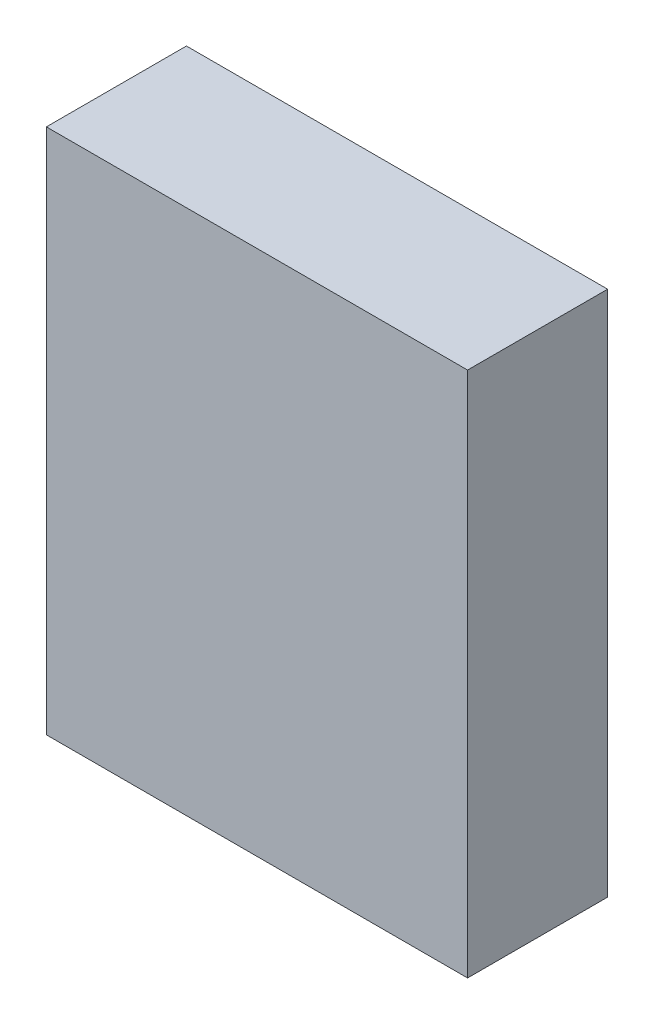
SolidWorks part; units mm, degrees
material "AISI 1045 Steel, cold drawn"
ref_plane "Front Plane" through (0, 0, 0) normal (0, 0, 1) x (1, 0, 0)
ref_plane "Top Plane" through (0, 0, 0) normal (0, 1, 0) x (1, 0, 0)
ref_plane "Right Plane" through (0, 0, 0) normal (1, 0, 0) x (0, 0, -1)
sketch "Sketch1" plane through (0, 0, 0) normal (0, 0, 1) x (1, 0, 0)
  line L1 (200, -250) -> (-200, -250)
  line L2 (200, -250) -> (200, 250)
  line L3 (200, 250) -> (-200, 250)
  line L4 (-200, -250) -> (-200, 250)
  line L5 (200, -250) -> (-200, 250) construction
  line L6 (200, 250) -> (-200, -250) construction
  point P0 (0, 0)
  dimension "D1" = 500
  dimension "D2" = 400
extrude "Boss-Extrude1" add sketch "Sketch1" along normal blind 150
sketch "Sketch2" plane through (0, 0, 0) normal (0, 0, -1) x (-1, 0, 0)
  line L1 (177.5, -230) -> (-177.5, -230)
  line L2 (177.5, -230) -> (177.5, 230)
  line L3 (177.5, 230) -> (-177.5, 230)
  line L4 (200, -250) -> (200, 250)
  line L5 (200, 250) -> (-200, 250)
  line L6 (-200, 250) -> (-200, -250)
  line L7 (-200, -250) -> (200, -250)
  line L8 (200, -250) -> (200, 250)
  line L9 (200, 250) -> (-200, 250)
  line L10 (-200, 250) -> (-200, -250)
  line L11 (-200, -250) -> (200, -250)
  line L12 (-177.5, -230) -> (-177.5, 230)
  line L13 (177.5, -230) -> (-177.5, 230) construction
  line L14 (177.5, 230) -> (-177.5, -230) construction
  point P2 (0, 0)
  dimension "D2" = 355
  dimension "D3" = 460
  dimension "D1" = 0
extrude "Cut-Extrude1" cut sketch "Sketch2" against normal blind 17
shell "Shell1" thickness 1.5
sketch "Sketch3" plane through (0, 0, 148.5) normal (0, 0, -1) x (-1, 0, 0)
  line L1 (162.5, -202.5) -> (-162.5, -202.5) construction
  line L2 (162.5, -202.5) -> (162.5, 202.5) construction
  line L3 (162.5, 202.5) -> (-162.5, 202.5) construction
  line L4 (-162.5, -202.5) -> (-162.5, 202.5) construction
  line L5 (162.5, -202.5) -> (-162.5, 202.5) construction
  line L6 (162.5, 202.5) -> (-162.5, -202.5) construction
  circle A0 centre (-162.5, 202.5) radius 7.5
  circle A1 centre (162.5, 202.5) radius 7.5
  circle A2 centre (162.5, -202.5) radius 7.5
  circle A3 centre (-162.5, -202.5) radius 7.5
  point P0 (0, 0)
  dimension "D3" = 15
  dimension "D1" = 325
  dimension "D2" = 405
extrude "Boss-Extrude2" add sketch "Sketch3" along normal blind 14
